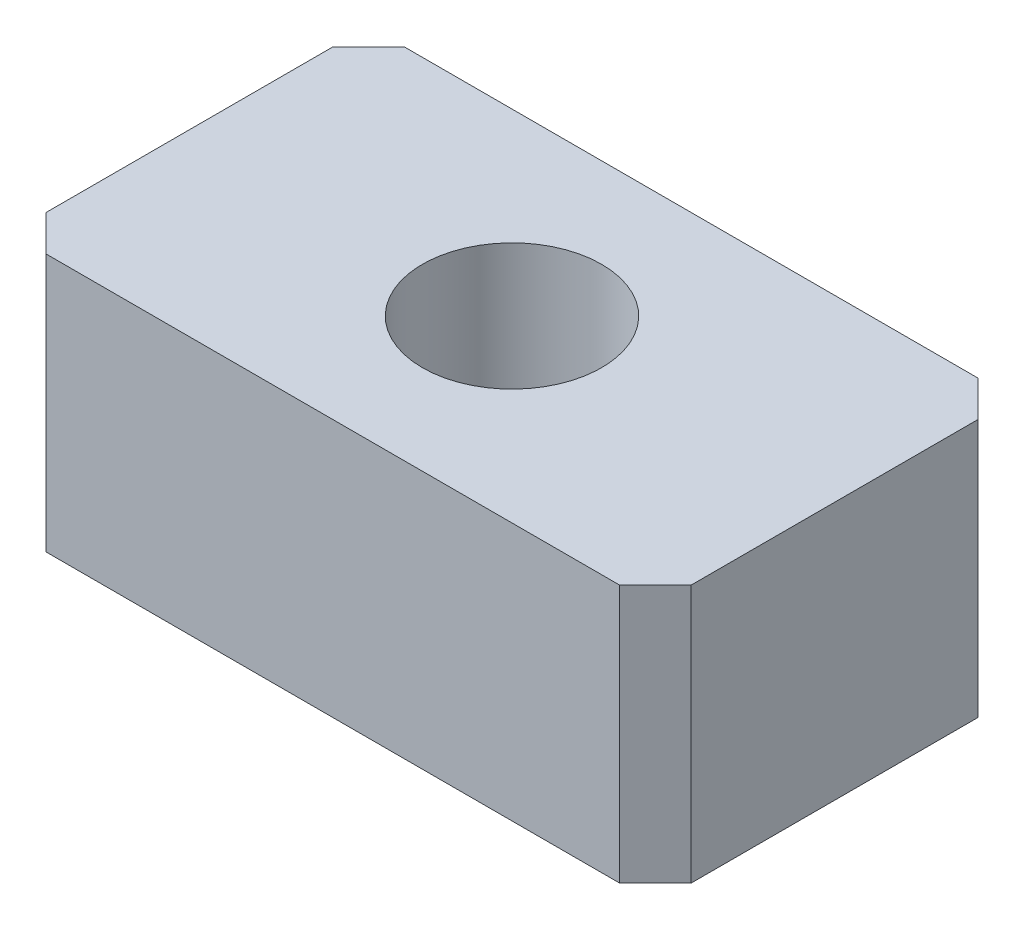
SolidWorks part; units mm, degrees
ref_plane "Front Plane" through (0, 0, 0) normal (0, 0, 1) x (1, 0, 0)
ref_plane "Top Plane" through (0, 0, 0) normal (0, 1, 0) x (1, 0, 0)
ref_plane "Right Plane" through (0, 0, 0) normal (1, 0, 0) x (0, 0, -1)
sketch "Sketch1" plane through (0, 0, 0) normal (0, 1, 0) x (1, 0, 0)
  line L1 (0, 0) -> (-18, 0)
  line L2 (0, 0) -> (0, 10)
  line L3 (0, 10) -> (-18, 10)
  line L4 (-18, 0) -> (-18, 10)
  dimension "D1" = 18
  dimension "D2" = 10
extrude "Boss-Extrude1" add sketch "Sketch1" along normal blind 7.2
sketch "Sketch2" plane through (0, 7.2, 0) normal (0, 1, 0) x (1, 0, 0)
  line L0 (0, 0) -> (0, 10) construction
  line L1 (0, 10) -> (-18, 10) construction
  circle A0 centre (-9, 5) radius 2.5
  dimension "D2" = 5
  dimension "D3" = 5
  dimension "D1" = 9
extrude "Cut-Extrude1" cut sketch "Sketch2" against normal through all
chamfer "Chamfer1" distance 1 angle 45 4 edges at (-18, 3.6, -10) (0, 3.6, -10) (0, 3.6, 0) (-18, 3.6, 0)
